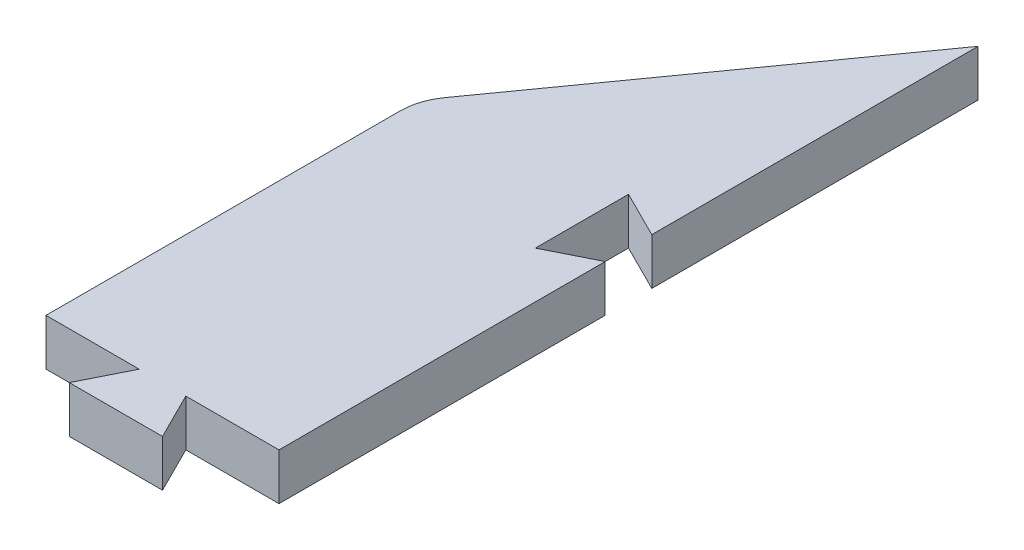
SolidWorks part; units mm, degrees
ref_plane "Спереди" through (0, 0, 0) normal (0, 0, 1) x (1, 0, 0)
ref_plane "Сверху" through (0, 0, 0) normal (0, 1, 0) x (1, 0, 0)
ref_plane "Справа" through (0, 0, 0) normal (1, 0, 0) x (0, 0, -1)
sketch "Эскиз1" plane through (0, 0, 0) normal (0, 1, 0) x (1, 0, 0)
  line L1 (10, -17.5) -> (2, -17.5)
  line L2 (10, -17.5) -> (10, 10.5)
  line L3 (-9.0687, 15.8039) -> (10, 42.5)
  line L4 (-10, -17.5) -> (-10, 12.8977)
  line L5 (-4, -21.5) -> (4, -21.5)
  line L6 (4, -21.5) -> (2, -17.5)
  line L7 (-4, -21.5) -> (-2, -17.5)
  line L8 (-2, -17.5) -> (-10, -17.5)
  line L12 (10, -3.5) -> (10, 24.4799) construction
  line L13 (10, 42.5) -> (10, 52.0644) construction
  line L14 (6, 8.5) -> (10, 10.5)
  line L16 (0, -12.2343) -> (0, 16.5) construction
  line L20 (10, 14.5) -> (10, 42.5)
  line L22 (6, 16.5) -> (6, 8.5)
  line L23 (6, 16.5) -> (10, 14.5)
  arc A0 (-10, 12.8977) -> (-9.0687, 15.8039) centre (-5, 12.8977) cw
  point P3 (-10, 25)
  dimension "D1" = 42.5
  dimension "D5" = 5
  dimension "D2" = 20
  dimension "D3" = 60
  dimension "D4" = 8
  dimension "D6" = 4
extrude "Бобышка-Вытянуть1" add sketch "Эскиз1" along normal blind 4 contours L4 A0 L3 L20 L23 L22 L14 L2 L1 L6 L5 L7 L8
